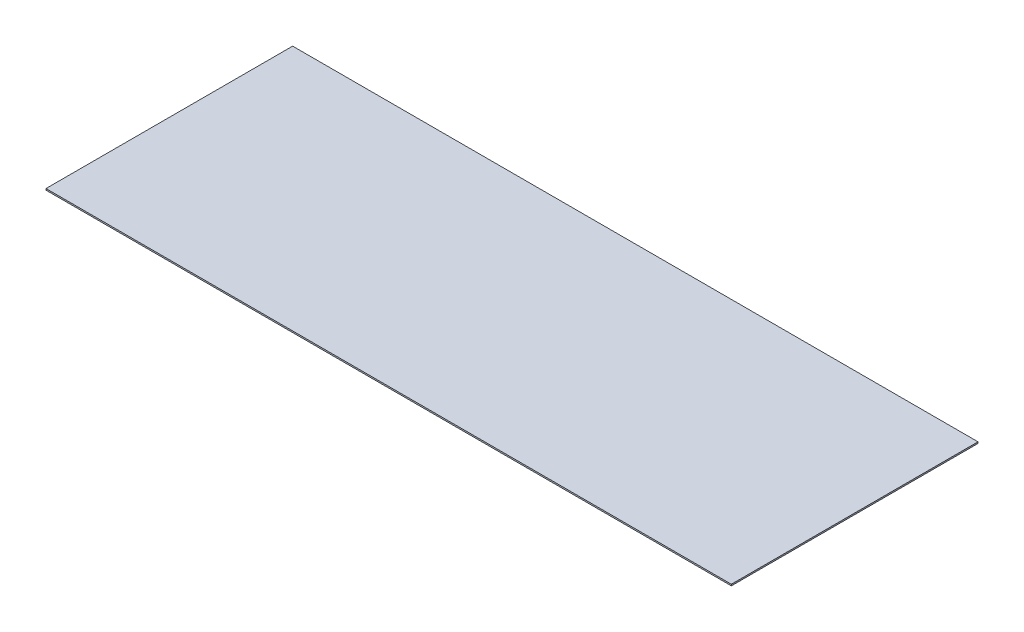
SolidWorks part; units mm, degrees
ref_plane "前视基准面" through (0, 0, 0) normal (0, 0, 1) x (1, 0, 0)
ref_plane "上视基准面" through (0, 0, 0) normal (0, 1, 0) x (1, 0, 0)
ref_plane "右视基准面" through (0, 0, 0) normal (1, 0, 0) x (0, 0, -1)
other "Configuration Table"
sketch "草图1" plane through (0, 0, 0) normal (0, 0, 1) x (1, 0, 0)
  line L0 (-3, -3) -> (1403, -3)
  line L1 (1403, -3) -> (1403, 0)
  line L2 (1403, 0) -> (-3, 0)
  line L3 (-3, 0) -> (-3, -3)
extrude "304_floor_1400x500_t3" add sketch "草图1" along normal blind 506 from offset 3 separate body
